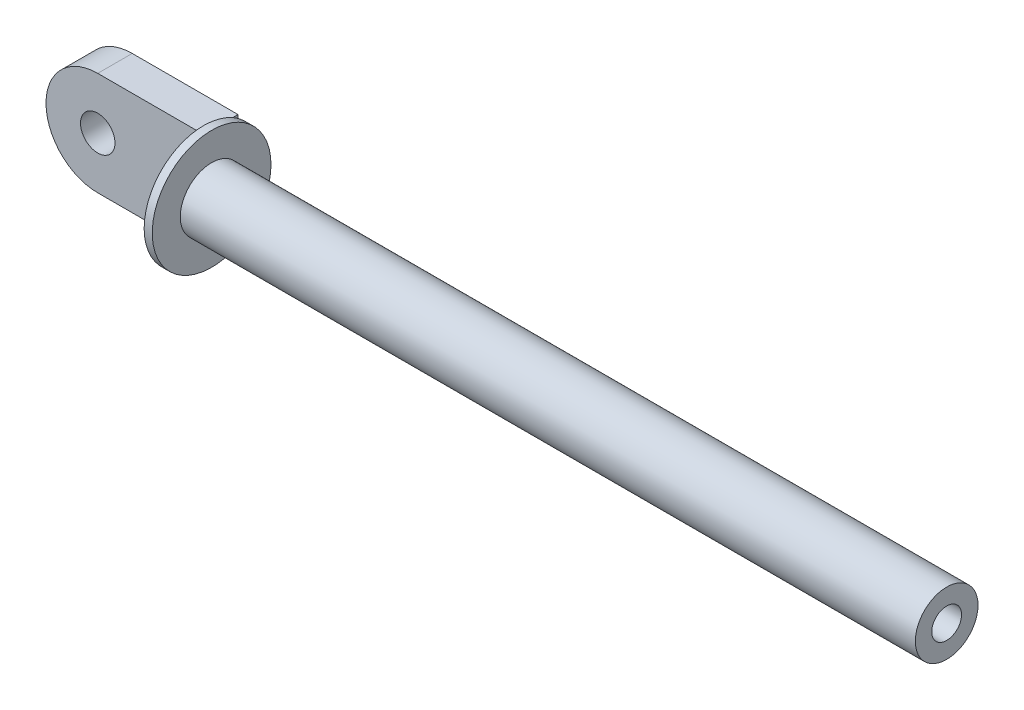
SolidWorks part; units mm, degrees
ref_plane "Front Plane" through (0, 0, 0) normal (0, 0, 1) x (1, 0, 0)
ref_plane "Top Plane" through (0, 0, 0) normal (0, 1, 0) x (1, 0, 0)
ref_plane "Right Plane" through (0, 0, 0) normal (1, 0, 0) x (0, 0, -1)
sketch "Sketch1" plane through (0, 0, 0) normal (0, 0, 1) x (1, 0, 0)
  line L1 (-83.738, 45.7845) -> (-53.0742, 45.7845)
  line L3 (-83.738, 15.7845) -> (-53.0742, 15.7845)
  line L4 (-53.0742, 45.7845) -> (-53.0742, 15.7845)
  circle A0 centre (-83.738, 30.7845) radius 5
  arc A1 (-83.738, 45.7845) -> (-83.738, 15.7845) centre (-83.738, 30.7845) ccw
  point P7 (0, 0)
  dimension "D1" = 10
  dimension "D2" = 30
extrude "Boss-Extrude1" add sketch "Sketch1" along normal mid plane 10
sketch "Sketch2" plane through (0, 0, 5) normal (0, 0, 1) x (1, 0, 0)
  line L0 (-53.0742, 45.7845) -> (-53.0742, 47.9978)
  line L1 (-53.0742, 45.7845) -> (-83.738, 45.7845) construction
  line L2 (-53.0742, 47.9978) -> (-50.7284, 47.9978)
  line L3 (-50.7284, 47.9978) -> (-50.7284, 39.8692)
  line L4 (-50.7284, 39.8692) -> (162.3605, 39.8692)
  line L5 (162.3605, 39.8692) -> (162.3605, 35.1075)
  line L6 (162.3605, 35.1075) -> (-48.6588, 35.1075)
  line L7 (-48.6588, 35.1075) -> (-48.6588, 30.7845)
  line L8 (-48.6588, 30.7845) -> (-53.0742, 30.7845)
  line L9 (-53.0742, 15.7845) -> (-53.0742, 45.7845) construction
  line L10 (-53.0742, 30.7845) -> (-53.0742, 45.7845)
revolve "Revolve1" add sketch "Sketch2" angle 360 about L8
